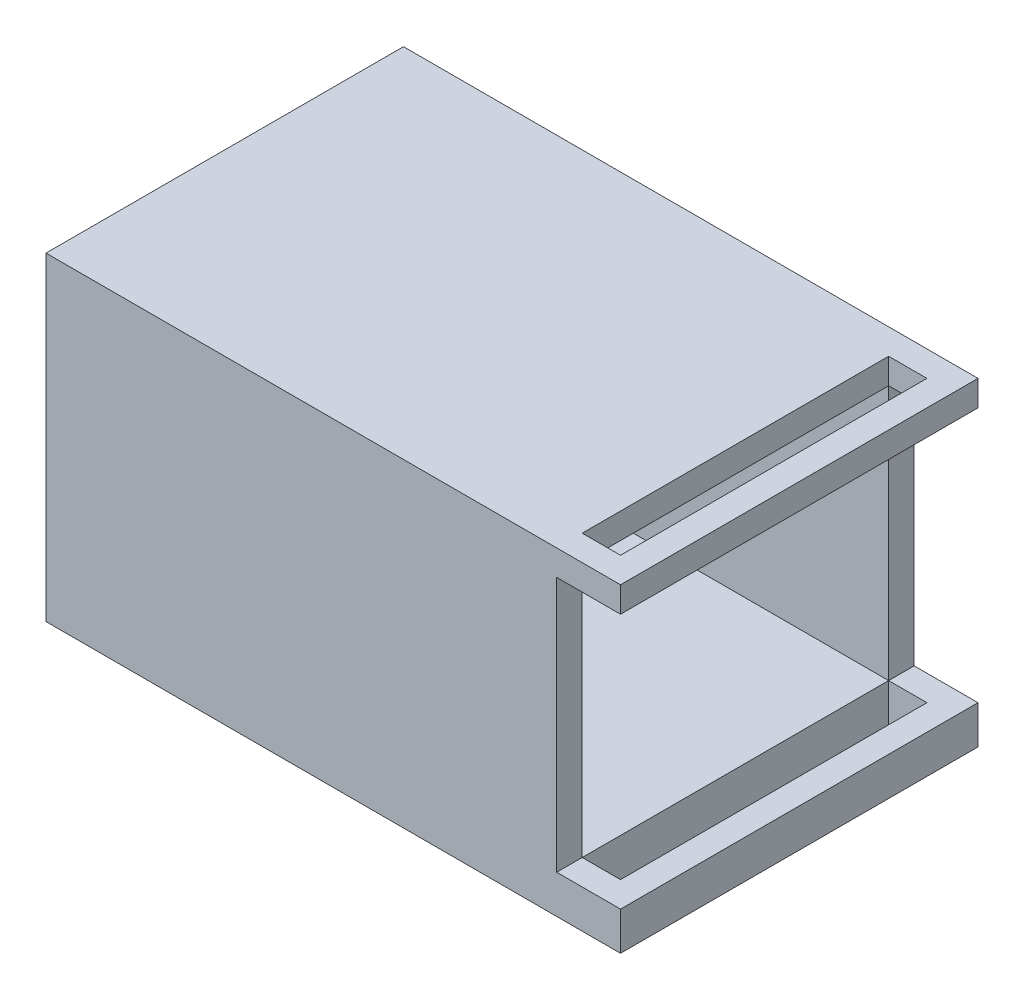
SolidWorks part; units mm, degrees
ref_plane "Front Plane" through (0, 0, 0) normal (0, 0, 1) x (1, 0, 0)
ref_plane "Top Plane" through (0, 0, 0) normal (0, 1, 0) x (1, 0, 0)
ref_plane "Right Plane" through (0, 0, 0) normal (1, 0, 0) x (0, 0, -1)
sketch "Sketch1" plane through (0, 0, 0) normal (0, 1, 0) x (1, 0, 0)
  line L1 (0, 0) -> (45, 0)
  line L2 (0, 0) -> (0, 28)
  line L3 (0, 28) -> (45, 28)
  line L4 (45, 0) -> (45, 28)
  dimension "D1" = 28
  dimension "D2" = 45
extrude "Boss-Extrude1" add sketch "Sketch1" along normal blind 3 contours L2 L1 L4 L3
sketch "Sketch2" plane through (0, 3, 0) normal (0, 1, 0) x (1, 0, 0)
  line L0 (40, 26) -> (40, 28)
  line L1 (0, 28) -> (40, 28)
  line L2 (0, 28) -> (0, 0)
  line L3 (0, 0) -> (40, 0)
  line L5 (2, 26) -> (40, 26)
  line L6 (2, 26) -> (2, 2)
  line L7 (2, 2) -> (40, 2)
  line L9 (40, 2) -> (40, 0)
  line L10 (45, 0) -> (45, 28) construction
  line L11 (0, 0) -> (45, 0) construction
  dimension "D1" = 2
  dimension "D2" = 2
  dimension "D3" = 2
  dimension "D4" = 5
  dimension "D5" = 5
extrude "Boss-Extrude2" add sketch "Sketch2" along normal blind 22 contours L5 L0 L1 L2 L3 L9 L7 L6
sketch "Sketch4" plane through (0, 25, 0) normal (0, 1, 0) x (1, 0, 0)
  line L0 (0, 28) -> (40, 28) construction
  line L1 (0, 28) -> (45, 28)
  line L2 (0, 28) -> (0, 0)
  line L3 (0, 0) -> (45, 0)
  line L4 (45, 28) -> (45, 0)
  line L5 (2, 2) -> (40, 2) construction
  line L6 (40, 26) -> (43, 26)
  line L7 (40, 26) -> (40, 2)
  line L8 (40, 2) -> (43, 2)
  line L9 (43, 26) -> (43, 2)
  dimension "D1" = 2
extrude "Boss-Extrude4" add sketch "Sketch4" against normal blind 2
sketch "Sketch5" plane through (0, 0, 0) normal (-1, 0, 0) x (0, 0, 1)
  line L0 (-18.72, 5.25) -> (-18.72, 5.96)
  line L1 (-17.47, 4) -> (-10.53, 4)
  line L2 (-17.47, 7.21) -> (-10.53, 7.21)
  line L3 (-9.28, 5.96) -> (-9.28, 5.25)
  line L4 (0, 0) -> (-28, 0) construction
  line L5 (-28, 25) -> (-28, 0) construction
  line L6 (0, 25) -> (0, 0) construction
  line L7 (-18.5, 12.5) -> (-9.5, 12.5)
  line L8 (-18.5, 12.5) -> (-18.5, 8.5)
  line L9 (-18.5, 8.5) -> (-9.5, 8.5)
  line L10 (-9.5, 12.5) -> (-9.5, 8.5)
  arc A0 (-18.72, 5.25) -> (-17.47, 4) centre (-17.47, 5.25) ccw
  arc A1 (-17.47, 7.21) -> (-18.72, 5.96) centre (-17.47, 5.96) ccw
  arc A2 (-9.28, 5.96) -> (-10.53, 7.21) centre (-10.53, 5.96) ccw
  arc A3 (-10.53, 4) -> (-9.28, 5.25) centre (-10.53, 5.25) ccw
  dimension "D7" = 1.25
  dimension "D1" = 1.25
  dimension "D2" = 0.71
  dimension "D3" = 6.94
  dimension "D4" = 1.25
  dimension "D5" = 1.25
  dimension "D6" = 6.94
  dimension "D8" = 3.21
  dimension "D9" = 0.71
  dimension "D10" = 4
  dimension "D11" = 9.28
  dimension "D12" = 4
  dimension "D13" = 9
  dimension "D14" = 1.29
  dimension "D15" = 0.22
  dimension "D16" = 0.22
  dimension "D17" = 9.28
extrude "Cut-Extrude1" cut sketch "Sketch5" against normal blind 2
sketch "Sketch6" plane through (0, 3, 0) normal (0, 1, 0) x (1, 0, 0)
  line L0 (45, 0) -> (45, 28) construction
  line L1 (43, 2) -> (40, 2)
  line L2 (43, 2) -> (43, 26)
  line L3 (43, 26) -> (40, 26)
  line L4 (40, 2) -> (40, 26)
  line L5 (40, 0) -> (45, 0) construction
  line L6 (40, 28) -> (45, 28) construction
  line L7 (40, 26) -> (40, 28) construction
  dimension "D1" = 2
  dimension "D2" = 2
  dimension "D3" = 2
extrude "Cut-Extrude2" cut sketch "Sketch6" against normal blind 3
